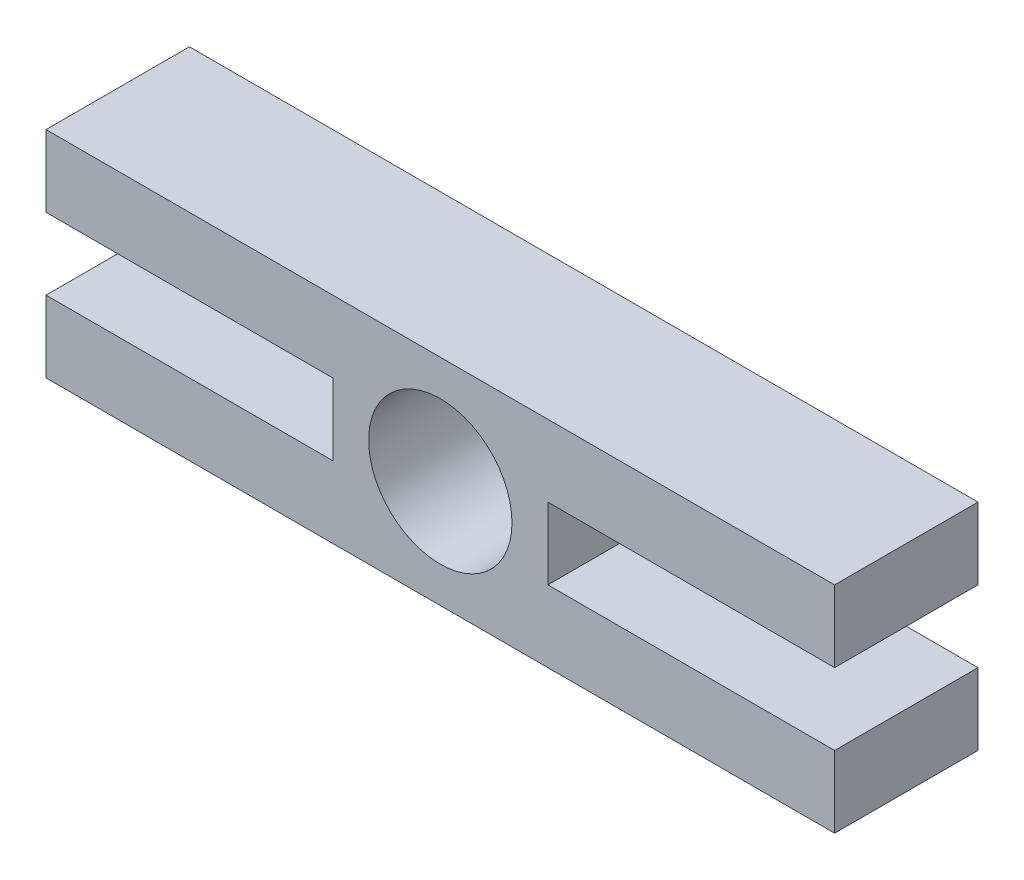
SolidWorks part; units mm, degrees
ref_plane "Front Plane" through (0, 0, 0) normal (0, 0, 1) x (1, 0, 0)
ref_plane "Top Plane" through (0, 0, 0) normal (0, 1, 0) x (1, 0, 0)
ref_plane "Right Plane" through (0, 0, 0) normal (1, 0, 0) x (0, 0, -1)
sketch "Sketch1" plane through (0, 0, 0) normal (0, 0, 1) x (1, 0, 0)
  line L1 (-50.8, 0) -> (-50.8, 6.35)
  line L2 (-50.8, 6.35) -> (0, 6.35)
  line L3 (0, 6.35) -> (0, 19.05)
  line L4 (0, 19.05) -> (-50.8, 19.05)
  line L5 (-50.8, 19.05) -> (-50.8, 25.4)
  line L7 (-50.8, 19.05) -> (-97.7976, 19.05) construction
  line L8 (-97.7976, 19.05) -> (-97.7976, 6.35) construction
  line L9 (-97.7976, 6.35) -> (-50.8, 6.35) construction
  line L10 (0, 12.7) -> (6.35, 12.7) construction
  line L11 (6.35, 12.7) -> (6.35, 4.7841) construction
  line L12 (31.75, 12.7) -> (31.75, 4.7841) construction
  line L13 (19.05, 25.4) -> (19.05, -5.9402) construction
  line L14 (88.9, 0) -> (88.9, 6.35)
  line L15 (88.9, 19.05) -> (88.9, 25.4)
  line L16 (38.1, 12.7) -> (31.75, 12.7) construction
  line L18 (38.1, 19.05) -> (88.9, 19.05)
  line L19 (38.1, 6.35) -> (38.1, 19.05)
  line L20 (88.9, 6.35) -> (38.1, 6.35)
  line L22 (19.05, 31.75) -> (-50.8, 31.75)
  line L23 (-50.8, 31.75) -> (-50.8, 25.4)
  line L24 (19.05, 31.75) -> (88.9, 31.75)
  line L25 (88.9, 31.75) -> (88.9, 25.4)
  line L26 (88.9, -6.35) -> (88.9, 0)
  line L27 (19.05, -6.35) -> (88.9, -6.35)
  line L28 (-50.8, -6.35) -> (-50.8, 0)
  line L29 (19.05, -6.35) -> (-50.8, -6.35)
  circle A0 centre (19.05, 12.7) radius 12.7
  circle A3 centre (19.05, 12.7) radius 19.05 construction
  dimension "D1" = 25.4
  dimension "D6" = 38.1
  dimension "D2" = 6.35
  dimension "D3" = 12.7
  dimension "D4" = 6.35
  dimension "D5" = 50.8
  dimension "D7" = 12.7
  dimension "D8" = 69.85
extrude "Boss-Extrude1" add sketch "Sketch1" along normal blind 25.4
